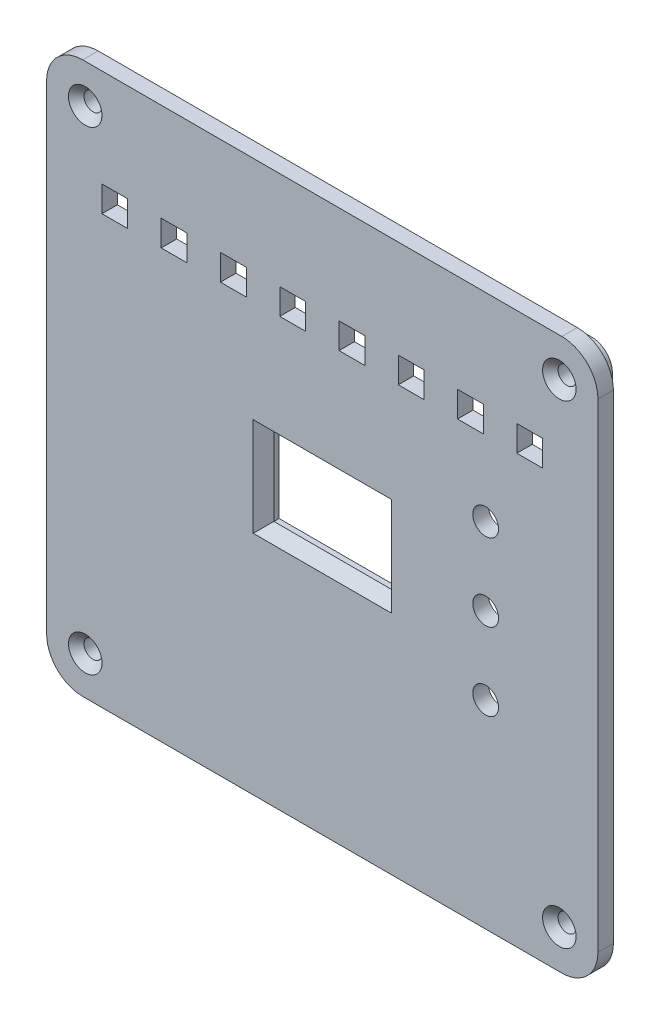
SolidWorks part; units mm, degrees
ref_plane "Piano frontale" through (0, 0, 0) normal (0, 0, 1) x (1, 0, 0)
ref_plane "Piano superiore" through (0, 0, 0) normal (0, 1, 0) x (1, 0, 0)
ref_plane "Piano destro" through (0, 0, 0) normal (1, 0, 0) x (0, 0, -1)
sketch "Schizzo1" plane through (0, 0, 126.0033) normal (0, 0, 1) x (1, 0, 0)
  line L0 (-77.6287, -48.2434) -> (15.3461, -48.2434) construction
  line L1 (-77.6287, 58.7314) -> (15.3461, 58.7314)
  line L2 (-84.6287, 51.7314) -> (-84.6287, -41.2434)
  line L3 (-77.6287, -48.2434) -> (15.3461, -48.2434)
  line L4 (22.3461, 51.7314) -> (22.3461, -41.2434)
  line L5 (15.3461, 58.7314) -> (-77.6287, 58.7314) construction
  line L6 (22.3461, -41.2434) -> (22.3461, 51.7314) construction
  line L7 (-84.6287, 51.7314) -> (-84.6287, -41.2434) construction
  arc A0 (-84.6287, 51.7314) -> (-77.6287, 58.7314) centre (-77.6287, 51.7314) cw
  arc A1 (15.3461, 58.7314) -> (22.3461, 51.7314) centre (15.3461, 51.7314) cw
  arc A2 (22.3461, -41.2434) -> (15.3461, -48.2434) centre (15.3461, -41.2434) cw
  arc A3 (-84.6287, -41.2434) -> (-77.6287, -48.2434) centre (-77.6287, -41.2434) ccw
  dimension "D1" = 7
  dimension "D2" = 7
  dimension "D3" = 7
  dimension "D4" = 7
  dimension "D5" = 0
  dimension "D6" = 0
  dimension "D7" = 0
  dimension "D8" = 0
extrude "Estrusione-Estrusione1" add sketch "Schizzo1" along normal blind 3
sketch "Schizzo2" plane through (0, 0, 129.0033) normal (0, 0, 1) x (1, 0, 0)
  circle A0 centre (-77.1414, 51.2441) radius 1.75
  circle A1 centre (14.8588, 51.2441) radius 1.75
  circle A2 centre (14.8588, -40.7561) radius 1.75
  circle A3 centre (-77.1287, -40.7686) radius 1.75
  dimension "D1" = 3.5
  dimension "D2" = 3.5
  dimension "D3" = 3.5
  dimension "D4" = 3.5
extrude "Taglio-Estrusione1" cut sketch "Schizzo2" against normal up to next
chamfer "Smusso1" distance 1.5 angle 45 4 edges at (-75.3787, -40.7686, 129.0033) (16.6088, -40.7561, 129.0033) (16.6088, 51.2441, 129.0033) (-75.3914, 51.2441, 129.0033)
sketch "Schizzo3" plane through (0, 0, 129.0033) normal (0, 0, 1) x (1, 0, 0)
  line L0 (-42.3361, 12.613) -> (-42.3361, -2.087) construction
  line L1 (-42.5361, 12.813) -> (-19.7465, 12.813)
  line L2 (-42.5361, 12.813) -> (-42.5361, -2.287)
  line L3 (-42.5361, -2.287) -> (-19.7465, -2.287)
  line L4 (-19.7465, 12.813) -> (-19.7465, -2.287)
  line L5 (-19.9465, 12.613) -> (-42.3361, 12.613) construction
  line L6 (-42.3361, -2.087) -> (-19.9465, -2.087) construction
  line L7 (-19.9465, -2.087) -> (-19.9465, 12.613) construction
  dimension "D1" = 0.2
  dimension "D2" = 0.2
  dimension "D3" = 0.2
  dimension "D4" = 0.2
extrude "Taglio-Estrusione2" cut sketch "Schizzo3" against normal through all
chamfer "Smusso2" distance 2 angle 45 4 edges at (-31.1413, -2.287, 129.0033) (-19.7465, 5.263, 129.0033) (-31.1413, 12.813, 129.0033) (-42.5361, 5.263, 129.0033)
sketch "Schizzo4" plane through (0, 0, 126.0033) normal (0, 0, -1) x (-1, 0, 0)
  line L0 (77.6287, 55.7314) -> (-15.3461, 55.7314) construction
  line L1 (-15.1461, 55.5314) -> (77.4287, 55.5314)
  line L2 (-19.1461, 51.5314) -> (-19.1461, -41.0434)
  line L3 (-15.1461, -45.0434) -> (77.4287, -45.0434)
  line L4 (81.4287, 51.5314) -> (81.4287, -41.0434)
  line L5 (-19.3461, 51.7314) -> (-19.3461, -41.2434) construction
  line L6 (81.6287, -41.2434) -> (81.6287, 51.7314) construction
  line L7 (-15.3461, -45.2434) -> (77.6287, -45.2434) construction
  line L9 (73.8385, -43.0434) -> (-11.5989, -43.0434)
  line L10 (79.4287, -37.496) -> (79.4287, 47.9407)
  line L11 (73.838, 53.5314) -> (-11.5991, 53.5314)
  line L12 (-17.1461, -37.4962) -> (-17.1461, 47.9843)
  arc A0 (-17.1461, 47.9843) -> (-11.5991, 53.5314) centre (-14.8588, 51.2441) ccw
  arc A1 (73.838, 53.5314) -> (79.4287, 47.9407) centre (77.1414, 51.2441) ccw
  arc A5 (-11.5989, -43.0434) -> (-17.1461, -37.4962) centre (-14.8588, -40.7561) ccw
  arc A6 (79.4287, -37.496) -> (73.8385, -43.0434) centre (77.1287, -40.7686) ccw
  arc A7 (81.4287, 51.5314) -> (77.4287, 55.5314) centre (77.4287, 51.5314) ccw
  arc A8 (-15.1461, 55.5314) -> (-19.1461, 51.5314) centre (-15.1461, 51.5314) ccw
  arc A9 (-19.1461, -41.0434) -> (-15.1461, -45.0434) centre (-15.1461, -41.0434) ccw
  arc A10 (81.4287, -41.0434) -> (77.4287, -45.0434) centre (77.4287, -41.0434) cw
  circle A11 centre (77.1287, -40.7686) radius 1.75
  circle A12 centre (-14.8588, -40.7561) radius 1.75
  circle A13 centre (-14.8588, 51.2441) radius 1.75
  circle A14 centre (77.1414, 51.2441) radius 1.75
  circle M21 centre (77.1287, -40.7686) radius 1.75
  circle M22 centre (-14.8588, -40.7561) radius 1.75
  circle M23 centre (-14.8588, 51.2441) radius 1.75
  circle M24 centre (77.1414, 51.2441) radius 1.75
  dimension "D9" = 4
  dimension "D10" = 4
  dimension "D11" = 4
  dimension "D12" = 4
  dimension "D1" = 0.2
  dimension "D2" = 0.2
  dimension "D3" = 0.2
  dimension "D4" = 0.2
  dimension "D5" = 2
  dimension "D6" = 2
  dimension "D7" = 2
  dimension "D8" = 2
extrude "Estrusione-Estrusione2" add sketch "Schizzo4" along normal blind 3 contours A10 L4 A7 L1 A8 L2 A9 L3 L10 A6 L9 A5 L12 A0 L11 A1 M21 M23 M24 M22
sketch "Schizzo5" plane through (0, 0, 129.0033) normal (0, 0, 1) x (1, 0, 0)
  line L0 (-69.5413, 35.694) -> (-69.5413, 38.794) construction
  line L1 (-73.8913, 39.744) -> (-68.8913, 39.744)
  line L2 (-73.8913, 39.744) -> (-73.8913, 34.744)
  line L3 (-73.8913, 34.744) -> (-68.8913, 34.744)
  line L4 (-68.8913, 39.744) -> (-68.8913, 34.744)
  line L5 (-69.5413, 38.794) -> (-73.2413, 38.794) construction
  line L6 (-62.3913, 39.744) -> (-57.3913, 39.744)
  line L7 (-62.3913, 39.744) -> (-62.3913, 34.744)
  line L8 (-62.3913, 34.744) -> (-57.3913, 34.744)
  line L9 (-57.3913, 39.744) -> (-57.3913, 34.744)
  line L10 (-58.0413, 38.794) -> (-61.7413, 38.794) construction
  line L11 (-58.0413, 35.694) -> (-58.0413, 38.794) construction
  line L12 (-50.8913, 39.744) -> (-45.8913, 39.744)
  line L13 (-50.8913, 39.744) -> (-50.8913, 34.744)
  line L14 (-50.8913, 34.744) -> (-45.8913, 34.744)
  line L15 (-45.8913, 39.744) -> (-45.8913, 34.744)
  line L16 (-39.3913, 39.744) -> (-34.3913, 39.744)
  line L17 (-39.3913, 39.744) -> (-39.3913, 34.744)
  line L18 (-39.3913, 34.744) -> (-34.3913, 34.744)
  line L19 (-34.3913, 39.744) -> (-34.3913, 34.744)
  line L20 (-46.5413, 35.694) -> (-46.5413, 38.794) construction
  line L21 (-46.5413, 38.794) -> (-50.2413, 38.794) construction
  line L23 (-35.0413, 38.794) -> (-38.7413, 38.794) construction
  line L24 (-35.0413, 35.694) -> (-35.0413, 38.794) construction
  line L25 (-27.8913, 39.744) -> (-22.8913, 39.744)
  line L26 (-27.8913, 39.744) -> (-27.8913, 34.744)
  line L27 (-27.8913, 34.744) -> (-22.8913, 34.744)
  line L28 (-22.8913, 39.744) -> (-22.8913, 34.744)
  line L29 (-16.3912, 39.744) -> (-11.3912, 39.744)
  line L30 (-16.3912, 39.744) -> (-16.3912, 34.744)
  line L31 (-16.3912, 34.744) -> (-11.3912, 34.744)
  line L32 (-11.3912, 39.744) -> (-11.3912, 34.744)
  line L33 (-4.8912, 39.744) -> (0.1088, 39.744)
  line L34 (-4.8912, 39.744) -> (-4.8912, 34.744)
  line L35 (-4.8912, 34.744) -> (0.1088, 34.744)
  line L36 (0.1088, 39.744) -> (0.1088, 34.744)
  line L37 (6.6088, 39.744) -> (11.6088, 39.744)
  line L38 (6.6088, 39.744) -> (6.6088, 34.744)
  line L39 (6.6088, 34.744) -> (11.6088, 34.744)
  line L40 (11.6088, 39.744) -> (11.6088, 34.744)
  line L41 (-23.5413, 38.794) -> (-27.2413, 38.794) construction
  line L42 (-23.5413, 35.694) -> (-23.5413, 38.794) construction
  line L43 (-12.0412, 35.694) -> (-12.0412, 38.794) construction
  line L44 (-12.0412, 38.794) -> (-15.7412, 38.794) construction
  line L45 (-0.5412, 35.694) -> (-0.5412, 38.794) construction
  line L46 (-0.5412, 38.794) -> (-4.2412, 38.794) construction
  line L47 (10.9588, 35.694) -> (10.9588, 38.794) construction
  line L48 (10.9588, 38.794) -> (7.2588, 38.794) construction
  circle A0 centre (0.5568, -9.7561) radius 2.5
  arc A2 (-3.2932, -12.0061) -> (-2.0932, -12.0061) centre (-2.6932, -12.0061) ccw construction
  arc A3 (-2.0932, -12.0061) -> (-3.2932, -12.0061) centre (-2.6932, -12.0061) ccw construction
  circle A4 centre (0.5568, 5.244) radius 2.5
  arc A5 (-3.2932, 2.994) -> (-2.0932, 2.994) centre (-2.6932, 2.994) ccw construction
  arc A6 (-2.0932, 2.994) -> (-3.2932, 2.994) centre (-2.6932, 2.994) ccw construction
  circle A7 centre (0.5568, 20.244) radius 2.5
  arc A8 (-3.2932, 17.994) -> (-2.0932, 17.994) centre (-2.6932, 17.994) ccw construction
  arc A9 (-2.0932, 17.994) -> (-3.2932, 17.994) centre (-2.6932, 17.994) ccw construction
  dimension "D33" = 5
  dimension "D34" = 3.25
  dimension "D35" = 2.25
  dimension "D37" = 2.25
  dimension "D38" = 5
  dimension "D41" = 5
  dimension "D1" = 5
  dimension "D2" = 5
  dimension "D3" = 0.65
  dimension "D4" = 0.95
  dimension "D5" = 5
  dimension "D6" = 0.95
  dimension "D7" = 5
  dimension "D8" = 0.65
  dimension "D9" = 5
  dimension "D10" = 5
  dimension "D11" = 0.65
  dimension "D12" = 0.95
  dimension "D13" = 5
  dimension "D14" = 5
  dimension "D15" = 0.95
  dimension "D16" = 0.65
  dimension "D17" = 5
  dimension "D18" = 5
  dimension "D19" = 5
  dimension "D20" = 5
  dimension "D21" = 5
  dimension "D22" = 5
  dimension "D23" = 5
  dimension "D24" = 5
  dimension "D25" = 0.95
  dimension "D26" = 0.65
  dimension "D27" = 0.65
  dimension "D28" = 0.95
  dimension "D29" = 0.65
  dimension "D30" = 0.95
  dimension "D31" = 0.65
  dimension "D32" = 0.95
  dimension "D36" = 3.25
  dimension "D39" = 3.25
  dimension "D40" = 2.25
extrude "Taglio-Estrusione3" cut sketch "Schizzo5" against normal through all and the other way through all
